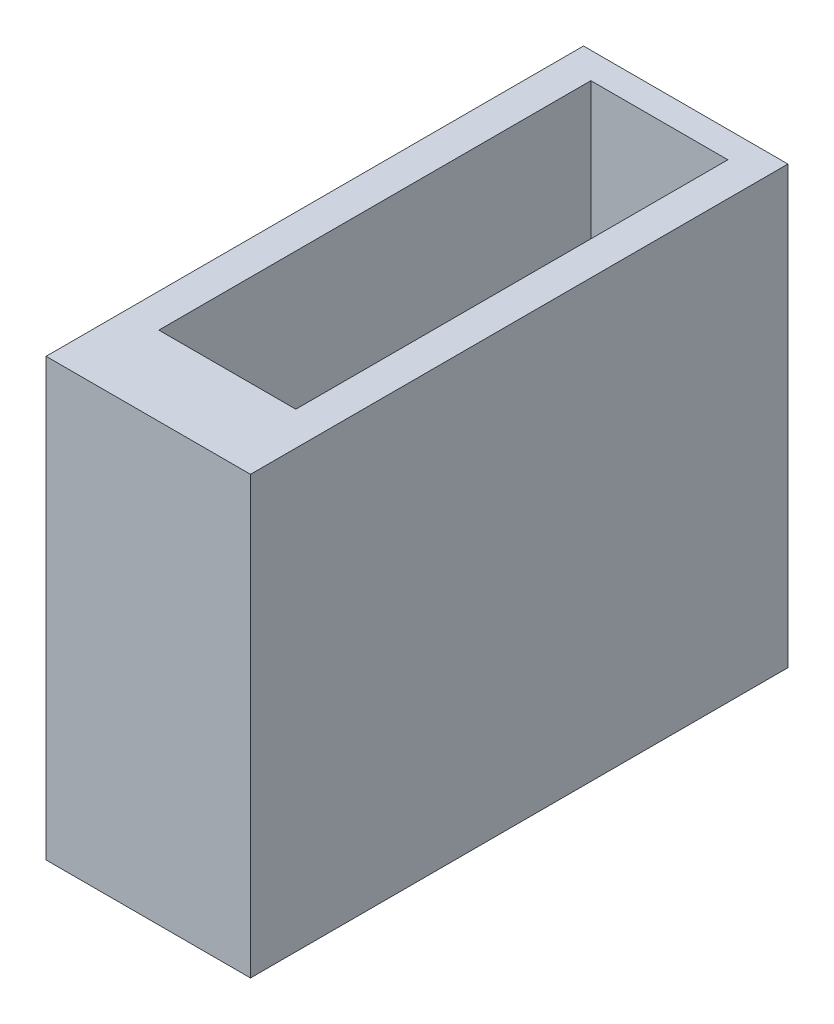
SolidWorks part; units mm, degrees
ref_plane "Front Plane" through (0, 0, 0) normal (0, 0, 1) x (1, 0, 0)
ref_plane "Top Plane" through (0, 0, 0) normal (0, 1, 0) x (1, 0, 0)
ref_plane "Right Plane" through (0, 0, 0) normal (1, 0, 0) x (0, 0, -1)
sketch "Sketch1" plane through (0, 0, 0) normal (0, 0, 1) x (1, 0, 0)
  line L0 (-26.9127, 27.2842) -> (11.8873, 27.2842)
  line L1 (-26.9127, -55.5058) -> (11.8873, -55.5058)
  line L2 (-26.9127, -55.5058) -> (-26.9127, 27.2842)
  line L4 (11.8873, -55.5058) -> (11.8873, 27.2842)
  dimension "D1" = 38.8
extrude "Boss-Extrude1" add sketch "Sketch1" along normal blind 102
sketch "Sketch2" plane through (0, -55.5058, 0) normal (0, -1, 0) x (1, 0, 0)
  line L1 (-20.5127, 87) -> (5.4873, 87)
  line L2 (-20.5127, 87) -> (-20.5127, 5)
  line L3 (-20.5127, 5) -> (5.4873, 5)
  line L4 (5.4873, 87) -> (5.4873, 5)
  line L48 (-7.5127, 102) -> (-7.5127, 0) construction
  line L49 (-26.9127, 102) -> (11.8873, 102) construction
  line L50 (-26.9127, 0) -> (11.8873, 0) construction
  dimension "D1" = 82
  dimension "D2" = 5
  dimension "D3" = 26
  dimension "D4" = 13
extrude "Cut-Extrude1" cut sketch "Sketch2" against normal through all
sketch "Sketch3" plane through (0, 0, 0) normal (0, 0, -1) x (-1, 0, 0)
  line L0 (-11.8873, 27.2842) -> (26.9127, 27.2842) construction
  circle A0 centre (7.5127, 27.2842) radius 7
